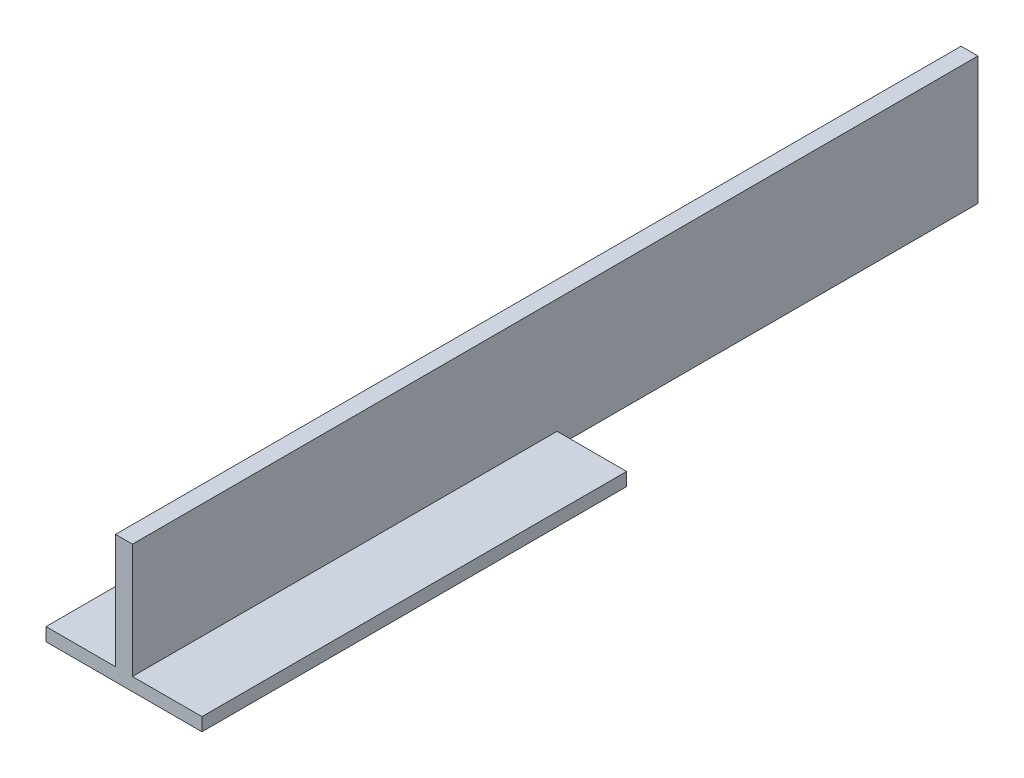
SolidWorks part; units mm, degrees
ref_plane "Plan de face" through (0, 0, 0) normal (0, 0, 1) x (1, 0, 0)
ref_plane "Plan de dessus" through (0, 0, 0) normal (0, 1, 0) x (1, 0, 0)
ref_plane "Plan de droite" through (0, 0, 0) normal (1, 0, 0) x (0, 0, -1)
sketch "Esquisse1" plane through (0, 0, 0) normal (0, 0, 1) x (1, 0, 0)
  line L0 (0, 0) -> (83, 0)
  line L1 (83, 0) -> (83, 7)
  line L2 (83, 7) -> (46, 7)
  line L3 (46, 7) -> (46, 68)
  line L4 (46, 68) -> (37, 68)
  line L5 (37, 68) -> (37, 7)
  line L6 (37, 7) -> (0, 7)
  line L7 (0, 7) -> (0, 0)
  dimension "D1" = 7
  dimension "D2" = 9
  dimension "D3" = 83
  dimension "D4" = 68
extrude "Boss.-Extru.1" add sketch "Esquisse1" along normal blind 450
sketch "Esquisse2" plane through (0, 7, 0) normal (0, 1, 0) x (1, 0, 0)
  line L1 (83, 0) -> (46, 0)
  line L2 (46, 0) -> (46, -224)
  line L3 (83, -224) -> (83, 0)
  line L5 (83, -450) -> (83, 0) construction
  line L6 (83, -224) -> (46, -224)
  line L10 (46, -450) -> (46, 0) construction
  dimension "D3" = 224
extrude "Enlèv. mat.-Extru.1" cut sketch "Esquisse2" against normal up to vertex (7 mm away) up to point (83, 0, 0)
